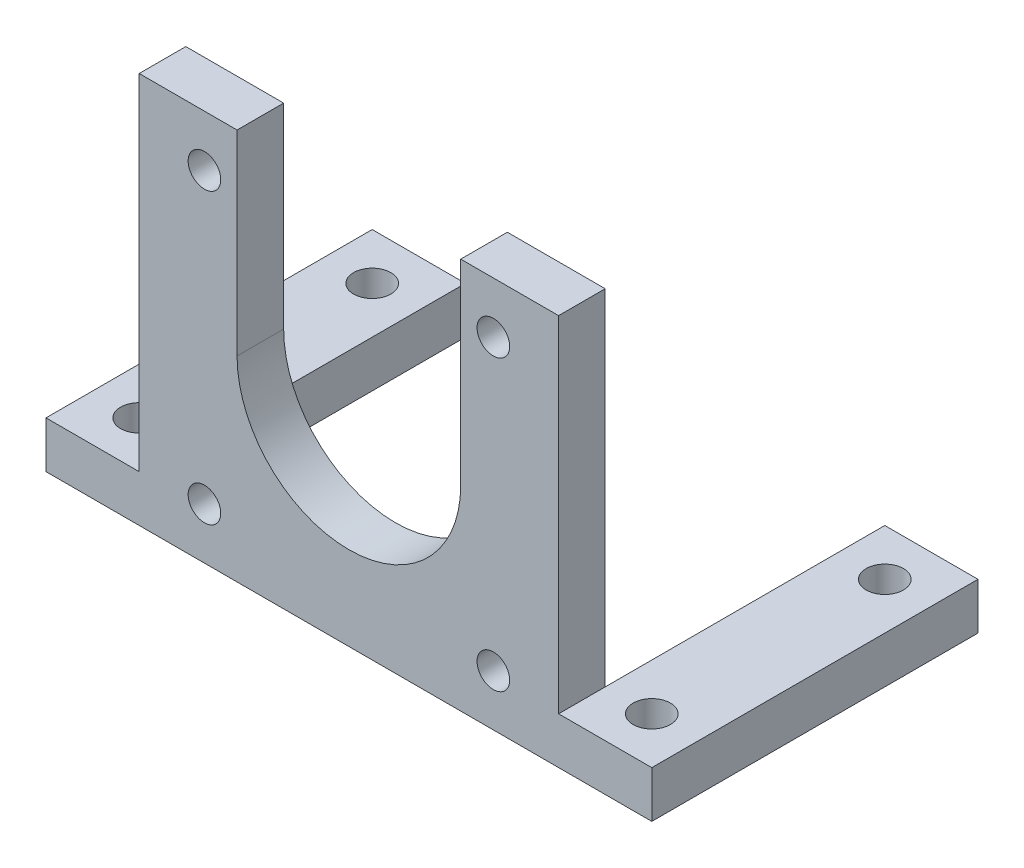
SolidWorks part; units mm, degrees
material "ABS"
ref_plane "Plano frontal" through (0, 0, 0) normal (0, 0, 1) x (1, 0, 0)
ref_plane "Plano superior" through (0, 0, 0) normal (0, 1, 0) x (1, 0, 0)
ref_plane "Plano direito" through (0, 0, 0) normal (1, 0, 0) x (0, 0, -1)
sketch "Esboço1" plane through (0, 0, 0) normal (0, 0, 1) x (1, 0, 0)
  line L0 (-12, 0) -> (-12, 21)
  line L1 (-22.5, 21) -> (-12, 21)
  line L2 (-22.5, 21) -> (-22.5, -21)
  line L3 (-22.5, -21) -> (22.5, -21)
  line L4 (22.5, 21) -> (22.5, -21)
  line L5 (-22.5, 21) -> (22.5, -21) construction
  line L6 (-22.5, -21) -> (22.5, 21) construction
  line L7 (12, 0) -> (12, 21)
  line L8 (12, 21) -> (22.5, 21)
  line L10 (-15.5, 15.5) -> (15.5, 15.5) construction
  line L11 (-15.5, 15.5) -> (-15.5, -15.5) construction
  line L12 (-15.5, -15.5) -> (15.5, -15.5) construction
  line L13 (15.5, 15.5) -> (15.5, -15.5) construction
  line L14 (-15.5, 15.5) -> (15.5, -15.5) construction
  line L15 (-15.5, -15.5) -> (15.5, 15.5) construction
  arc A0 (-12, 0) -> (12, 0) centre (0, 0) ccw
  circle A1 centre (-15.5, 15.5) radius 1.75
  circle A2 centre (15.5, 15.5) radius 1.75
  circle A3 centre (15.5, -15.5) radius 1.75
  circle A4 centre (-15.5, -15.5) radius 1.75
  point P0 (0, 0)
  dimension "D2" = 24
  dimension "D4" = 3.5
  dimension "D1" = 45
  dimension "D3" = 31
  dimension "D5" = 42
extrude "Ressalto-extrusão1" add sketch "Esboço1" along normal blind 5
sketch "Esboço2" plane through (0, -21, 0) normal (0, -1, 0) x (1, 0, 0)
  line L0 (-32.5, 5) -> (-22.5, 5)
  line L2 (0, 5) -> (0, -35.0506) construction
  line L3 (27.5, 0) -> (27.5, -25) construction
  line L4 (32.5, -30) -> (32.5, 5)
  line L5 (22.5, -30) -> (32.5, -30)
  line L6 (-22.5, 5) -> (-22.5, -30)
  line L7 (-22.5, -30) -> (-32.5, -30)
  line L8 (-32.5, -30) -> (-32.5, 5)
  line L9 (-22.5, 5) -> (22.5, 5) construction
  line L11 (-27.5, 0) -> (-27.5, -25) construction
  line L12 (22.5, 5) -> (22.5, -30)
  line L13 (32.5, 5) -> (22.5, 5)
  circle A0 centre (-27.5, -25) radius 2
  circle A1 centre (-27.5, 0) radius 2
  circle A2 centre (27.5, 0) radius 2
  circle A3 centre (27.5, -25) radius 2
  point P5 (0, 5)
  point P20 (-27.5, -12.5)
  point P21 (-32.5, -12.5)
  point P22 (-27.5, -30)
  dimension "D3" = 25
  dimension "D4" = 4
  dimension "D1" = 10
  dimension "D2" = 35
extrude "Ressalto-extrusão2" add sketch "Esboço2" against normal blind 5
